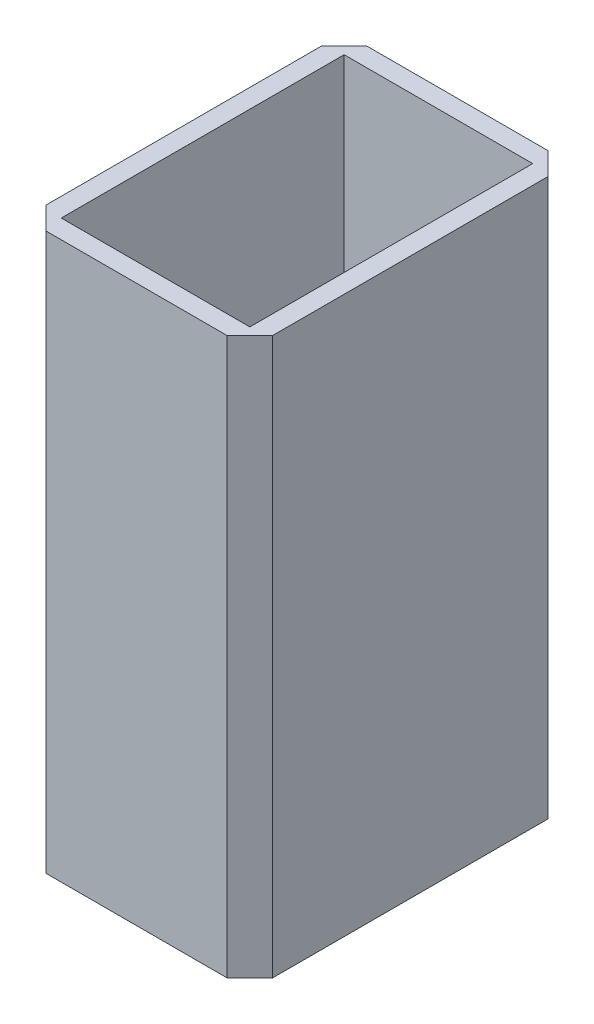
SolidWorks part; units mm, degrees
ref_plane "Front Plane" through (0, 0, 0) normal (0, 0, 1) x (1, 0, 0)
ref_plane "Top Plane" through (0, 0, 0) normal (0, 1, 0) x (1, 0, 0)
ref_plane "Right Plane" through (0, 0, 0) normal (1, 0, 0) x (0, 0, -1)
sketch "Sketch1" plane through (0, 0, 0) normal (0, 1, 0) x (1, 0, 0)
  line L1 (-52.595, -10.6202) -> (-14.495, -10.6202)
  line L2 (-52.595, -10.6202) -> (-52.595, -64.5952)
  line L3 (-52.595, -64.5952) -> (-14.495, -64.5952)
  line L4 (-14.495, -10.6202) -> (-14.495, -64.5952)
  dimension "D1" = 53.975
  dimension "D2" = 38.1
extrude "Boss-Extrude1" add sketch "Sketch1" along normal blind 3.175
sketch "Sketch2" plane through (0, 3.175, 0) normal (0, 1, 0) x (1, 0, 0)
  line L1 (-49.42, -13.7952) -> (-17.67, -13.7952)
  line L2 (-49.42, -13.7952) -> (-49.42, -61.4202)
  line L3 (-49.42, -61.4202) -> (-17.67, -61.4202)
  line L4 (-17.67, -13.7952) -> (-17.67, -61.4202)
  line L5 (-52.595, -10.6202) -> (-14.495, -10.6202)
  line L6 (-52.595, -10.6202) -> (-52.595, -64.5952)
  line L7 (-52.595, -64.5952) -> (-14.495, -64.5952)
  line L8 (-14.495, -10.6202) -> (-14.495, -64.5952)
  dimension "D1" = 3.175
  dimension "D2" = 3.175
  dimension "D3" = 3.175
  dimension "D4" = 3.175
extrude "Boss-Extrude2" add sketch "Sketch2" along normal blind 90.4875
chamfer "Chamfer1" distance 3.81 angle 45 4 edges at (-14.495, 46.8312, 64.5952) (-14.495, 46.8312, 10.6202) (-52.595, 46.8312, 64.5952) (-52.595, 46.8312, 10.6202)
